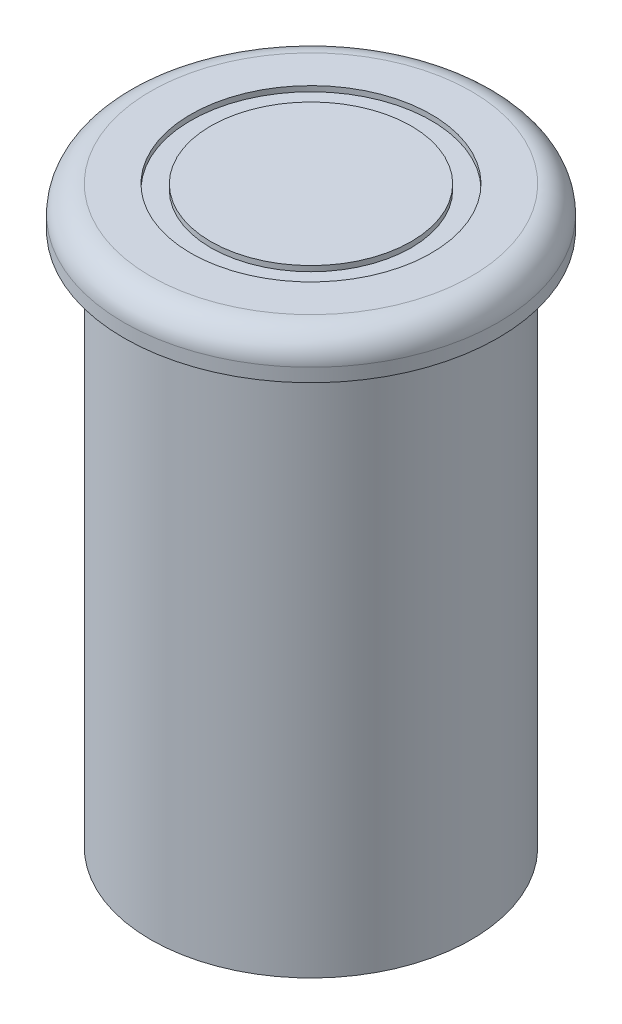
SolidWorks part; units mm, degrees
ref_plane "前视基准面" through (0, 0, 0) normal (0, 0, 1) x (1, 0, 0)
ref_plane "上视基准面" through (0, 0, 0) normal (0, 1, 0) x (1, 0, 0)
ref_plane "右视基准面" through (0, 0, 0) normal (1, 0, 0) x (0, 0, -1)
sketch "草图1" plane through (0, 0, 0) normal (0, 0, 1) x (1, 0, 0)
  line L0 (0, 0) -> (7, 0)
  line L1 (7, 0) -> (7, -1.5)
  line L2 (7, -1.5) -> (6, -1.5)
  line L3 (6, -1.5) -> (6, -21.5)
  line L4 (6, -21.5) -> (0, -21.5)
  line L5 (0, -21.5) -> (0, 0)
  line L6 (0, 0) -> (0, 3.583) construction
  dimension "D1" = 14
  dimension "D2" = 12
  dimension "D3" = 1.5
  dimension "D4" = 20
revolve "旋转1" add sketch "草图1" angle 360 about L6
fillet "圆角1" radius 1 1 edges at (0, 0, -7)
sketch "草图2" plane through (0, 0, 0) normal (0, 1, 0) x (1, 0, 0)
  circle A0 centre (0, 0) radius 4.5
  circle A1 centre (0, 0) radius 3.75
  dimension "D1" = 9
  dimension "D2" = 7.5
extrude "切除-拉伸1" cut sketch "草图2" against normal blind 0.2
